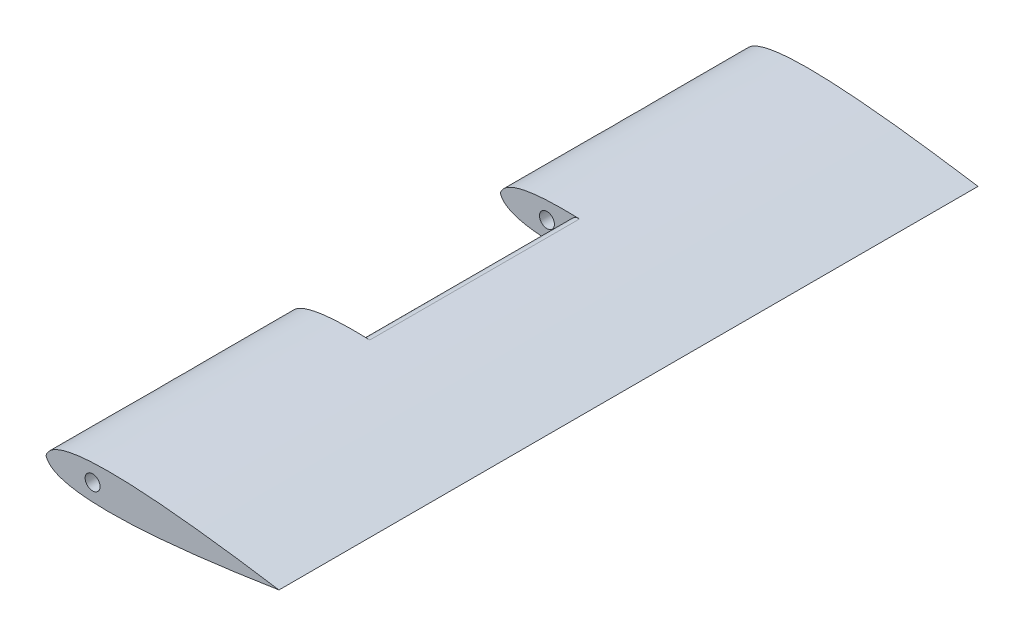
SolidWorks part; units mm, degrees
ref_plane "Front" through (0, 0, 0) normal (0, 0, 1) x (1, 0, 0)
ref_plane "Top" through (0, 0, 0) normal (0, 1, 0) x (1, 0, 0)
ref_plane "Right" through (0, 0, 0) normal (1, 0, 0) x (0, 0, -1)
sketch "Sketch1" plane through (0, 0, 0) normal (0, 1, 0) x (1, 0, 0)
  line L0 (-50, 0) -> (50, 0) construction
  line L1 (-96.3889, 75) -> (-46.3889, 75)
  line L2 (-96.3889, 75) -> (-96.3889, -75)
  line L3 (-96.3889, -75) -> (-46.3889, -75)
  line L4 (-46.3889, 75) -> (-46.3889, -75)
  line L7 (-96.3889, -22.5) -> (-81.3889, -22.5)
  line L8 (-96.3889, -22.5) -> (-96.3889, 22.5)
  line L9 (-96.3889, 22.5) -> (-81.3889, 22.5)
  line L10 (-81.3889, -22.5) -> (-81.3889, 22.5)
  point P4 (-46.3889, 0)
  point P11 (-96.3889, 0)
  point P12 (-81.3889, 0)
  dimension "D1" = 150
  dimension "D2" = 50
  dimension "D3" = 45
  dimension "D4" = 15
sketch "Sketch3" plane through (0, 0, 0) normal (0, 0, 1) x (1, 0, 0)
  line L0 (-96.3889, 0) -> (-46.3889, 0) construction
  line L1 (-96.3889, 0) -> (-46.3889, 0) construction
  line L2 (50, 0) -> (-50, 0) construction
  line L3 (-96.3889, 0) -> (-46.3889, 0) construction
  circle A0 centre (-86.3889, 0) radius 1.6
  spline S0 degree 2 poles (-96.3889, 0) (-94.2179, -7.5136) (-46.3889, 0) knots 0 0 0 1 1 1
  spline S1 degree 2 poles (-96.3889, 0) (-94.2179, 7.5136) (-46.3889, 0) knots 0 0 0 1 1 1
  point P2 (-86.3889, 0)
  point P12 (0, 0)
  point P13 (0, 0)
  point P17 (-86.9218, 0)
  point P18 (-86.3889, 0)
  dimension "D1" = 10
  dimension "D3" = 94.5615
  dimension "D2" = 3.2
  dimension "D4" = 2
extrude "Boss-Extrude1" add sketch "Sketch3" along normal up to vertex (75 mm away) and the other way up to vertex (75 mm away) up to point (-46.3889, 0, 75) other way up to point (-96.3889, 0, -75)
revolve "Cut-Revolve1" cut sketch "Sketch1" angle 360 about L2
fillet "Fillet1" radius 2 2 edges at (-81.8656, -3.7517, 0) (-81.8656, 3.7517, 0)
